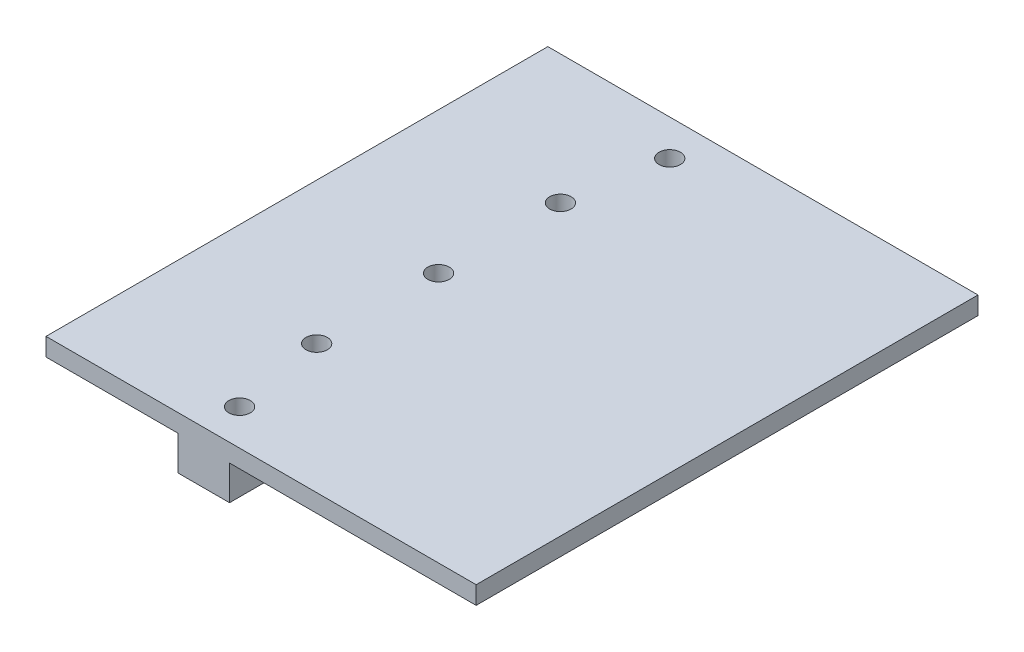
SolidWorks part; units mm, degrees
material "Custom Plastic"
ref_plane "Front Plane" through (0, 0, 0) normal (0, 0, 1) x (1, 0, 0)
ref_plane "Top Plane" through (0, 0, 0) normal (0, 1, 0) x (1, 0, 0)
ref_plane "Right Plane" through (0, 0, 0) normal (1, 0, 0) x (0, 0, -1)
sketch "Sketch1" plane through (0, 0, 0) normal (0, 1, 0) x (1, 0, 0)
  line L1 (-38.1, -44.45) -> (38.1, -44.45)
  line L2 (-38.1, -44.45) -> (-38.1, 44.45)
  line L3 (-38.1, 44.45) -> (38.1, 44.45)
  line L4 (38.1, -44.45) -> (38.1, 44.45)
  line L5 (-38.1, -44.45) -> (38.1, 44.45) construction
  line L6 (-38.1, 44.45) -> (38.1, -44.45) construction
  point P0 (0, 0)
  dimension "D1" = 76.2
  dimension "D2" = 88.9
extrude "Boss-Extrude1" add sketch "Sketch1" along normal blind 3.175
sketch "Sketch4" plane through (0, 0, 0) normal (0, -1, 0) x (1, 0, 0)
  line L0 (-10.16, 44.45) -> (-10.16, -44.45) construction
  line L1 (-38.1, 44.45) -> (38.1, 44.45) construction
  line L2 (38.1, -44.45) -> (-38.1, -44.45) construction
  line L3 (-38.1, -44.45) -> (-38.1, 44.45) construction
  line L5 (-14.732, 44.45) -> (-5.588, 44.45)
  line L6 (-14.732, 44.45) -> (-14.732, -44.45)
  line L7 (-14.732, -44.45) -> (-5.588, -44.45)
  line L8 (-5.588, 44.45) -> (-5.588, -44.45)
  dimension "D1" = 27.94
  dimension "D2" = 9.144
extrude "Boss-Extrude2" add sketch "Sketch4" along normal blind 6.096
hole_wizard "#6 Clearance Hole1" positions "3DSketch1" profile "Sketch2" hole size "#6" standard "ANSI Inch" end condition through all
sketch3d "3DSketch1"
  line L2 (-10.16, 3.175, -44.45) -> (-10.16, 3.175, 44.45) construction
  line L3 (38.1, 3.175, -44.45) -> (-38.1, 3.175, -44.45) construction
  line L4 (-38.1, 3.175, 44.45) -> (38.1, 3.175, 44.45) construction
  line L7 (-38.1, 3.175, -44.45) -> (-38.1, 3.175, 44.45) construction
  point P0 (-10.16, 3.175, -38.1)
  point P2 (-10.16, 3.175, 38.1)
  dimension "D3" = 6.35
  dimension "D2" = 6.35
  dimension "D1" = 27.94
sketch "Sketch2" plane through (-10.16, 3.175, -38.1) normal (1, 0, 0) x (0, 0, 1)
  line L0 (0, 0) -> (0, 9.271)
  line L1 (0, 9.271) -> (1.8986, 9.271)
  line L2 (1.8986, 9.271) -> (1.8986, 0)
  line L5 (1.8986, 0) -> (0, 0)
  line L11 (0, -6.35) -> (0, 107.95) construction
  dimension "Thru Hole Dia." = 3.7973
  dimension "Thru Hole Depth" = 9.271
sketch "Sketch5" plane through (0, -6.096, 0) normal (0, -1, 0) x (1, 0, 0)
  line L0 (-13.015, 44.45) -> (-13.015, -44.45) construction
  line L1 (-38.1, 44.45) -> (-14.732, 44.45) construction
  line L2 (-14.732, -44.45) -> (-38.1, -44.45) construction
  line L3 (-38.1, -44.45) -> (-38.1, 44.45) construction
  line L4 (-13.015, 0) -> (-38.1, 0) construction
  circle A0 centre (-13.015, 0) radius 5.08
  circle A1 centre (-13.015, 21.59) radius 5.08
  circle A2 centre (-13.015, -21.59) radius 5.08
  dimension "D3" = 10.16
  dimension "D1" = 25.085
  dimension "D2" = 43.18
extrude "Boss-Extrude3" add sketch "Sketch5" against normal up to surface (6.096 mm away) up to face at (-26.416, 0, 0)
hole_wizard "#6 Clearance Hole2" positions "3DSketch2" profile "Sketch3" hole size "#6" standard "ANSI Inch" end condition through all
sketch3d "3DSketch2"
  line L0 (-38.1, 3.175, 0) -> (38.1, 3.175, 0) construction
  line L1 (-38.1, 3.175, -44.45) -> (-38.1, 3.175, 44.45) construction
  line L2 (38.1, 3.175, 44.45) -> (38.1, 3.175, -44.45) construction
  point P0 (-13.015, 3.175, 0)
  point P2 (-13.015, 3.175, -21.59)
  point P4 (-13.015, 3.175, 21.59)
  point P13 (0, 0, 0)
  dimension "D2" = 21.59
  dimension "D1" = 43.18
  dimension "D4" = 25.085
sketch "Sketch3" plane through (-13.015, 3.175, 0) normal (1, 0, 0) x (0, 0, 1)
  line L0 (0, 0) -> (0, 9.271)
  line L1 (0, 9.271) -> (1.8986, 9.271)
  line L2 (1.8986, 9.271) -> (1.8986, 0)
  line L5 (1.8986, 0) -> (0, 0)
  line L11 (0, -6.35) -> (0, 107.95) construction
  dimension "Thru Hole Dia." = 3.7973
  dimension "Thru Hole Depth" = 9.271
equation "\"D3@3DSketch1\"=\"D2@3DSketch1\""
equation "\"D2@3DSketch2\"=\"D1@3DSketch2\"/2"
